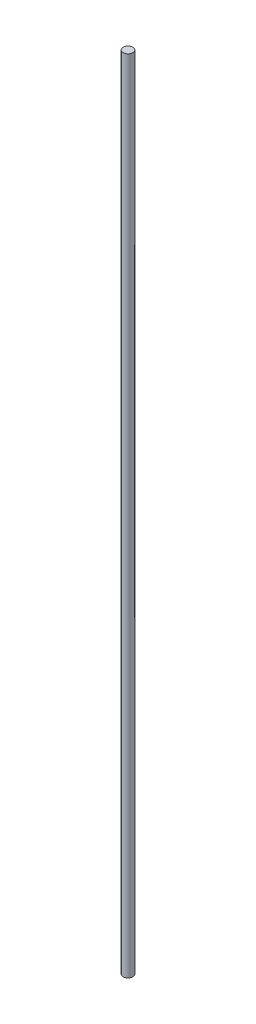
SolidWorks part; units mm, degrees
material "Polyethylene Cross-Linked"
ref_plane "Alzado" through (0, 0, 0) normal (0, 0, 1) x (1, 0, 0)
ref_plane "Planta" through (0, 0, 0) normal (0, 1, 0) x (1, 0, 0)
ref_plane "Vista lateral" through (0, 0, 0) normal (1, 0, 0) x (0, 0, -1)
sketch "Sketch1" plane through (0, 0, 0) normal (0, 0, 1) x (1, 0, 0)
  line L0 (0, -36) -> (0.75, -36)
  line L1 (0.75, -36) -> (0.75, -161)
  line L2 (0.75, -161) -> (0, -161)
  line L3 (0, -161) -> (0, -36)
  line L4 (0, -165) -> (0, -32) construction
revolve "Cuerdas_UHMWPE" add sketch "Sketch1" angle 360 about L4
